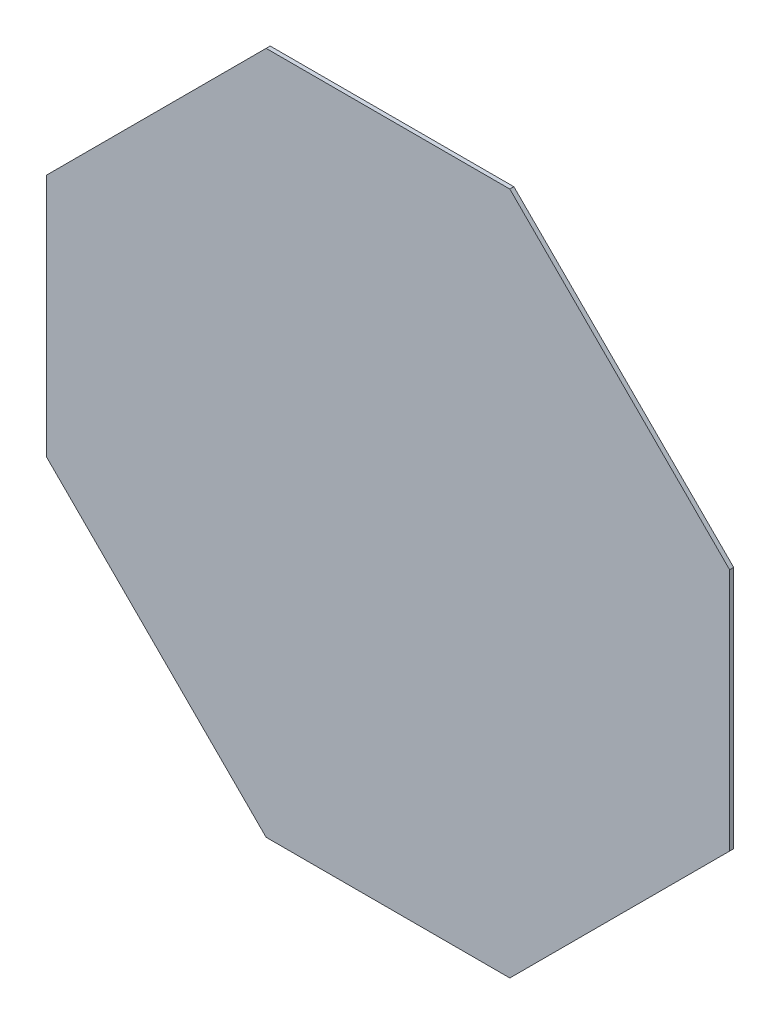
SolidWorks part; units mm, degrees
ref_plane "Front Plane" through (0, 0, 0) normal (0, 0, 1) x (1, 0, 0)
ref_plane "Top Plane" through (0, 0, 0) normal (0, 1, 0) x (1, 0, 0)
ref_plane "Right Plane" through (0, 0, 0) normal (1, 0, 0) x (0, 0, -1)
sketch "Sketch1" plane through (0, 0, 0) normal (0, 0, 1) x (1, 0, 0)
  line L44 (164, -159.7574) -> (1.2426, 3)
  line L45 (1.2426, 3) -> (-179.2426, 3)
  line L46 (-179.2426, 3) -> (-342, -159.7574)
  line L47 (-342, -159.7574) -> (-342, -340.2426)
  line L48 (-342, -340.2426) -> (-179.2426, -503)
  line L49 (-179.2426, -503) -> (1.2426, -503)
  line L50 (1.2426, -503) -> (164, -340.2426)
  line L51 (164, -340.2426) -> (164, -159.7574)
  line L52 (164, -159.7574) -> (1.2426, 3)
  line L53 (1.2426, 3) -> (-179.2426, 3)
  line L54 (-179.2426, 3) -> (-342, -159.7574)
  line L55 (-342, -159.7574) -> (-342, -340.2426)
  line L56 (-342, -340.2426) -> (-179.2426, -503)
  line L57 (-179.2426, -503) -> (1.2426, -503)
  line L58 (1.2426, -503) -> (164, -340.2426)
  line L59 (164, -340.2426) -> (164, -159.7574)
  dimension "D1" = 3
extrude "Boss-Extrude1" add sketch "Sketch1" along normal blind 3
